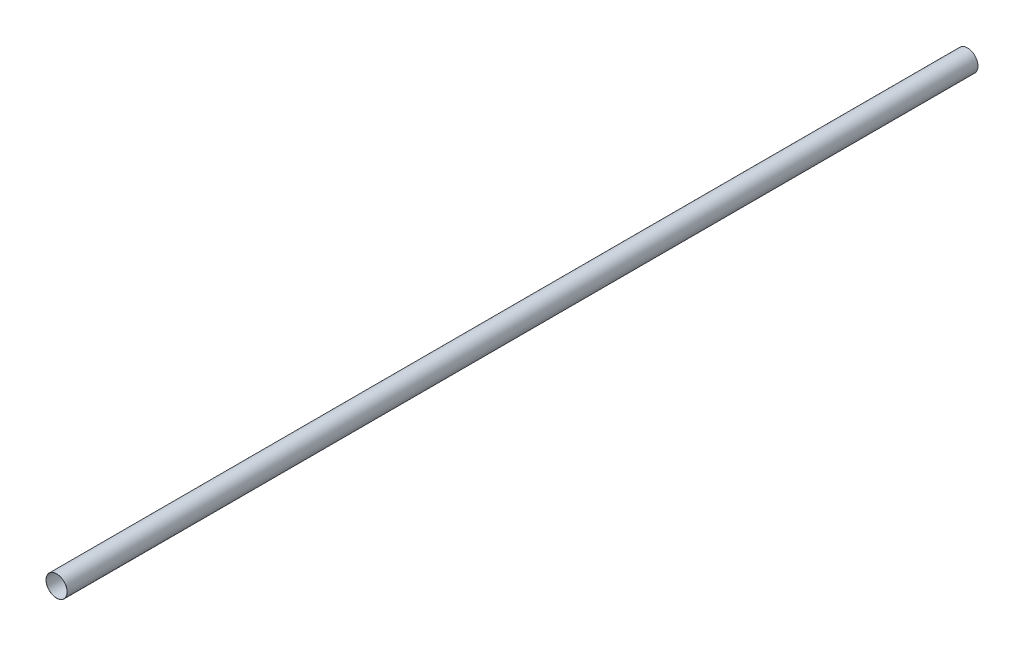
SolidWorks part; units mm, degrees
ref_plane "Front Plane" through (0, 0, 0) normal (0, 0, 1) x (1, 0, 0)
ref_plane "Top Plane" through (0, 0, 0) normal (0, 1, 0) x (1, 0, 0)
ref_plane "Right Plane" through (0, 0, 0) normal (1, 0, 0) x (0, 0, -1)
sketch "Sketch2" plane through (0, 0, 0) normal (0, 0, 1) x (1, 0, 0)
  circle A0 centre (0, 0) radius 9.525
  circle A1 centre (0, 0) radius 9.4488
  dimension "D1" = 19.05
  dimension "D2" = 0.0762
extrude "Boss-Extrude1" add sketch "Sketch2" along normal blind 820 contours A0
